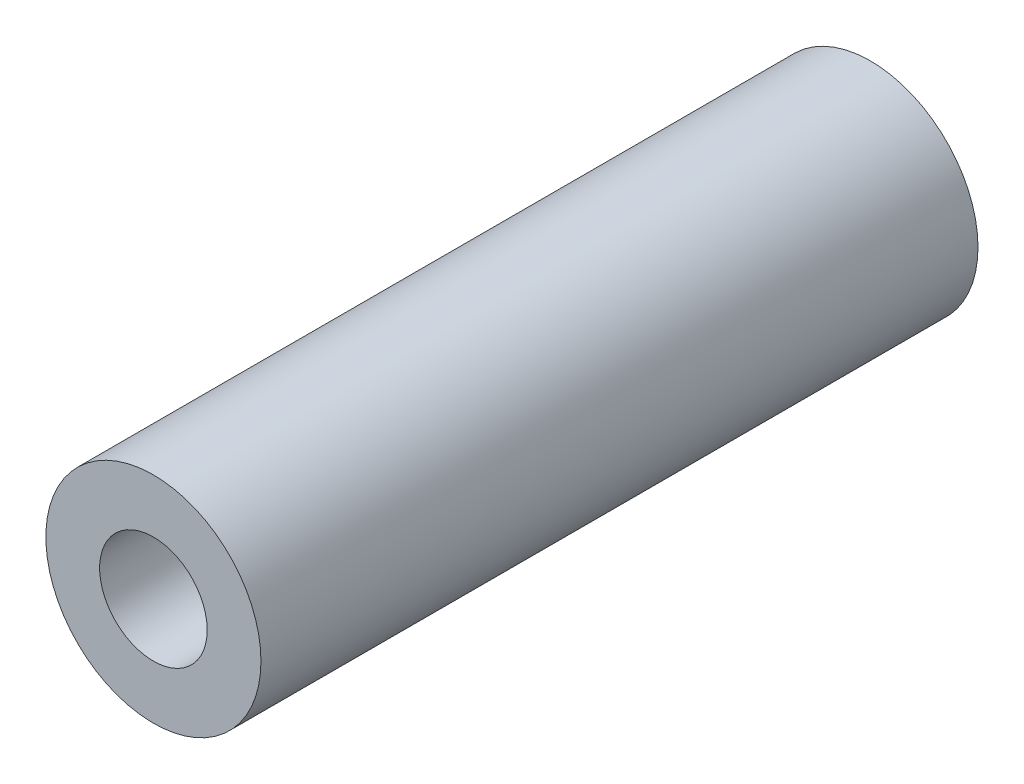
SolidWorks part; units mm, degrees
material "PPE"
ref_plane "Front Plane" through (0, 0, 0) normal (0, 0, 1) x (1, 0, 0)
ref_plane "Top Plane" through (0, 0, 0) normal (0, 1, 0) x (1, 0, 0)
ref_plane "Right Plane" through (0, 0, 0) normal (1, 0, 0) x (0, 0, -1)
sketch "Sketch1" plane through (0, 0, 0) normal (0, 0, 1) x (1, 0, 0)
  circle A0 centre (0, 0) radius 3
extrude "Boss-Extrude1" add sketch "Sketch1" along normal blind 20
sketch "Sketch2" plane through (0, 0, 0) normal (0, 0, -1) x (-1, 0, 0)
  circle A0 centre (0, 0) radius 1.5
sketch "Sketch3" plane through (0, 0, 20) normal (0, 0, 1) x (1, 0, 0)
  circle A0 centre (0, 0) radius 1.5
extrude "Cut-Extrude1" cut sketch "Sketch3" against normal through all
